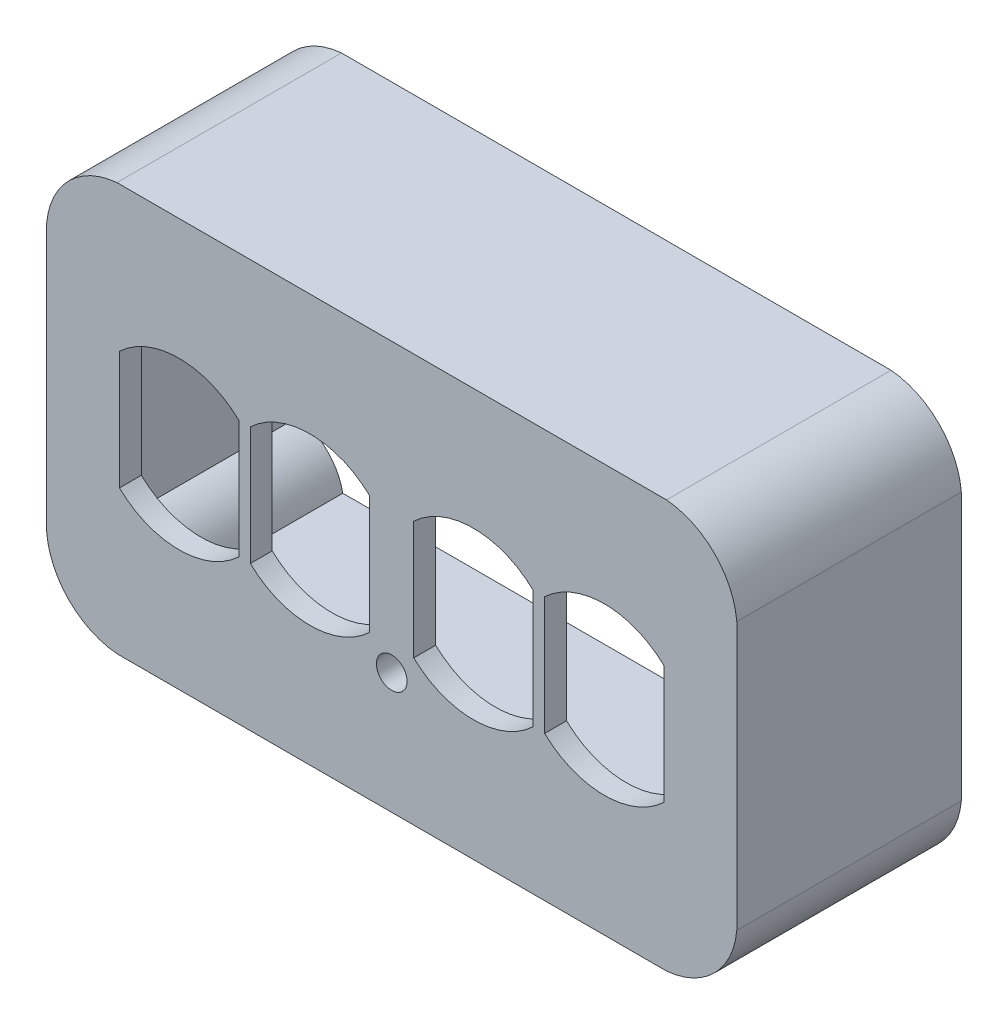
SolidWorks part; units mm, degrees
ref_plane "Спереди" through (0, 0, 0) normal (0, 0, 1) x (1, 0, 0)
ref_plane "Сверху" through (0, 0, 0) normal (0, 1, 0) x (1, 0, 0)
ref_plane "Справа" through (0, 0, 0) normal (1, 0, 0) x (0, 0, -1)
sketch "Эскиз1" plane through (0, 0, 0) normal (0, 0, 1) x (1, 0, 0)
  line L7 (-53, 27.25) -> (53, 27.25)
  line L8 (-53, 27.25) -> (-53, -27.25)
  line L9 (-53, -27.25) -> (53, -27.25)
  line L10 (53, 27.25) -> (53, -27.25)
  line L11 (-53, 27.25) -> (53, -27.25) construction
  line L12 (-53, -27.25) -> (53, 27.25) construction
  point P0 (0, 0)
  dimension "D1" = 106
  dimension "D2" = 54.5
extrude "Бобышка-Вытянуть1" add sketch "Эскиз1" along normal blind 4
sketch "Эскиз2" plane through (0, 0, 4) normal (0, 0, 1) x (1, 0, 0)
  line L0 (0, 0) -> (-53, 0) construction
  line L1 (-53, 27.25) -> (-53, -27.25) construction
  line L2 (-49.7193, 10.805) -> (-49.7193, -10.805)
  line L7 (-27.9193, 10.805) -> (-27.9193, -10.805)
  line L8 (-38.8193, 15.15) -> (-38.8193, -15.15) construction
  line L15 (-25.8193, 10.805) -> (-25.8193, -10.805)
  line L16 (-2.9193, -10.805) -> (0, 0) construction
  line L17 (0, 0) -> (0, -27.25) construction
  line L18 (-53, -27.25) -> (53, -27.25) construction
  line L19 (-4.0193, 10.805) -> (-4.0193, -10.805)
  line L20 (4.0193, 10.805) -> (4.0193, -10.805)
  line L21 (25.8193, 10.805) -> (25.8193, -10.805)
  line L22 (27.9193, 10.805) -> (27.9193, -10.805)
  line L23 (49.7193, 10.805) -> (49.7193, -10.805)
  circle A4 centre (0, -15.15) radius 2.8
  arc A5 (-49.7193, 10.805) -> (-27.9193, 10.805) centre (-38.8193, -0.6945) cw
  arc A6 (-49.7193, -10.805) -> (-27.9193, -10.805) centre (-38.8193, 0.6945) ccw
  arc A7 (-25.8193, -10.805) -> (-4.0193, -10.805) centre (-14.9193, 0.6945) ccw
  arc A8 (-25.8193, 10.805) -> (-4.0193, 10.805) centre (-14.9193, -0.6945) cw
  arc A9 (25.8193, 10.805) -> (4.0193, 10.805) centre (14.9193, -0.6945) ccw
  arc A10 (25.8193, -10.805) -> (4.0193, -10.805) centre (14.9193, 0.6945) cw
  arc A11 (49.7193, 10.805) -> (27.9193, 10.805) centre (38.8193, -0.6945) ccw
  arc A12 (49.7193, -10.805) -> (27.9193, -10.805) centre (38.8193, 0.6945) cw
  point P6 (-38.8193, 0)
  point P12 (-38.8193, 0)
  point P17 (-13.8193, 0)
  point P22 (-13.8193, 0)
  point P50 (13.8193, 0)
  point P51 (38.8193, 0)
  dimension "D4" = 5.6
  dimension "D1" = 2
  dimension "D2" = 2
extrude "Вырез-Вытянуть1" cut sketch "Эскиз2" against normal blind 4
sketch "Эскиз3" plane through (0, 0, 4) normal (0, 0, 1) x (1, 0, 0)
  line L4 (0, -37.25) -> (0, 37.25) construction
  line L5 (-63, 0) -> (63, 0) construction
  line L7 (-51.729, -26.2115) -> (51.729, -26.2115)
  line L8 (63, -37.25) -> (63, 37.25)
  line L9 (63, 37.25) -> (-63, 37.25)
  line L10 (-63, 37.25) -> (-63, -37.25)
  line L11 (-63, -37.25) -> (63, -37.25)
  line L12 (63, -24.4198) -> (63, 24.4198)
  line L13 (50.1698, 37.25) -> (-50.1698, 37.25)
  line L14 (-63, 24.4198) -> (-63, -24.4198)
  line L15 (-50.1698, -37.25) -> (50.1698, -37.25)
  line L16 (-51.729, -26.2115) -> (-51.729, 26.2115)
  line L17 (-51.729, 26.2115) -> (51.729, 26.2115)
  line L18 (51.729, -26.2115) -> (51.729, 26.2115)
  line L19 (-51.729, -26.2115) -> (51.729, 26.2115) construction
  line L20 (-51.729, 26.2115) -> (51.729, -26.2115) construction
  arc A0 (-50.1698, 37.25) -> (-63, 24.4198) centre (-48.9505, 23.2005) ccw
  arc A1 (50.1698, 37.25) -> (63, 24.4198) centre (48.9505, 23.2005) cw
  arc A2 (50.1698, -37.25) -> (63, -24.4198) centre (48.9505, -23.2005) ccw
  arc A3 (-50.1698, -37.25) -> (-63, -24.4198) centre (-48.9505, -23.2005) cw
  point P18 (0, 0)
  dimension "D1" = 10
extrude "Бобышка-Вытянуть2" add sketch "Эскиз3" against normal blind 41
sketch "Эскиз5" plane through (0, 0, -37) normal (0, 0, -1) x (-1, 0, 0)
  line L12 (-58, 24.1796) -> (-58, -24.1796)
  line L13 (-49.9296, -32.25) -> (49.9296, -32.25)
  line L14 (58, -24.1796) -> (58, 24.1796)
  line L15 (49.9296, 32.25) -> (-49.9296, 32.25)
  line L16 (-58, 24.1796) -> (-58, -24.1796)
  line L17 (-49.9296, -32.25) -> (49.9296, -32.25)
  line L18 (58, -24.1796) -> (58, 24.1796)
  line L19 (49.9296, 32.25) -> (-49.9296, 32.25)
  arc A12 (-49.9296, 32.25) -> (-58, 24.1796) centre (-48.9505, 23.2005) ccw
  arc A13 (-58, -24.1796) -> (-49.9296, -32.25) centre (-48.9505, -23.2005) ccw
  arc A14 (49.9296, -32.25) -> (58, -24.1796) centre (48.9505, -23.2005) ccw
  arc A15 (58, 24.1796) -> (49.9296, 32.25) centre (48.9505, 23.2005) ccw
  arc A16 (-49.9296, 32.25) -> (-58, 24.1796) centre (-48.9505, 23.2005) ccw
  arc A17 (-58, -24.1796) -> (-49.9296, -32.25) centre (-48.9505, -23.2005) ccw
  arc A18 (49.9296, -32.25) -> (58, -24.1796) centre (48.9505, -23.2005) ccw
  arc A19 (58, 24.1796) -> (49.9296, 32.25) centre (48.9505, 23.2005) ccw
  dimension "D1" = 5
extrude "Вырез-Вытянуть2" cut sketch "Эскиз5" against normal blind 36.7
sketch "Эскиз6" plane through (0, 0, -0.3) normal (0, 0, -1) x (-1, 0, 0)
  line L0 (-58, 24.1796) -> (-58, -24.1796) construction
  line L1 (0, 14.1847) -> (0, -8.8362) construction
  line L2 (-9.0583, 0) -> (12.3611, 0) construction
  arc A0 (-49.9296, 32.25) -> (-58, 24.1796) centre (-60.0205, 34.2705) cw
  arc A1 (-49.9296, 32.25) -> (-58, 24.1796) centre (-48.9505, 23.2005) ccw
  arc A2 (49.9296, 32.25) -> (58, 24.1796) centre (48.9505, 23.2005) cw
  arc A3 (49.9296, 32.25) -> (58, 24.1796) centre (60.0205, 34.2705) ccw
  arc A4 (49.9296, -32.25) -> (58, -24.1796) centre (60.0205, -34.2705) cw
  arc A5 (49.9296, -32.25) -> (58, -24.1796) centre (48.9505, -23.2005) ccw
  arc A6 (-49.9296, -32.25) -> (-58, -24.1796) centre (-48.9505, -23.2005) cw
  arc A7 (-49.9296, -32.25) -> (-58, -24.1796) centre (-60.0205, -34.2705) ccw
extrude "Бобышка-Вытянуть3" add sketch "Эскиз6" along normal up to vertex (36.7 mm away) up to point (49.9296, 32.25, -37)
sketch "Эскиз7" plane through (0, 0, -37) normal (0, 0, -1) x (-1, 0, 0)
  line L0 (-58, 24.1796) -> (-58, 32.1279) construction
  line L1 (-58, 32.1279) -> (-49.9296, 32.25) construction
  line L2 (-58, 32.1279) -> (-55.915, 29.9709) construction
  line L3 (0, 0) -> (0, 14.0973) construction
  line L4 (0, 0) -> (-14.0566, 0) construction
  circle A0 centre (-55.915, 29.9709) radius 1.6
  circle A1 centre (55.915, 29.9709) radius 1.6
  circle A2 centre (55.915, -29.9709) radius 1.6
  circle A3 centre (-55.915, -29.9709) radius 1.6
  dimension "D1" = 3.2
  dimension "D2" = 3
extrude "Вырез-Вытянуть3" cut sketch "Эскиз7" against normal blind 20
